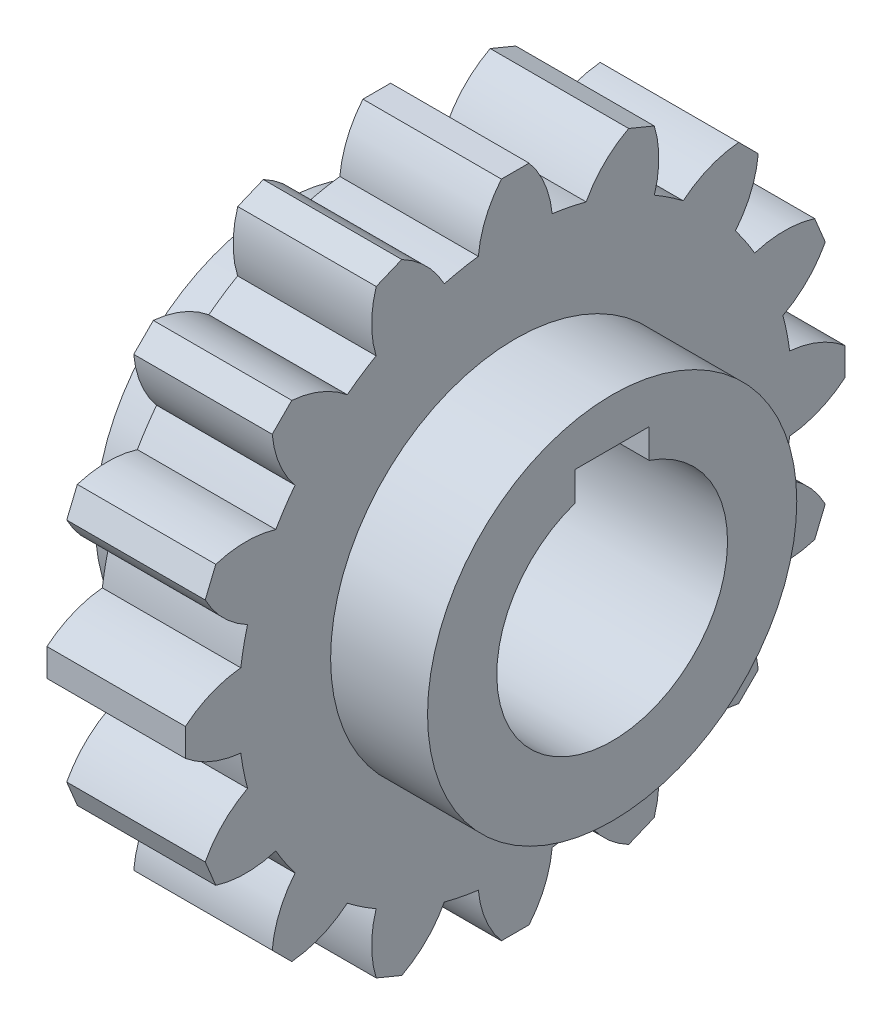
SolidWorks part; units mm, degrees
ref_plane "Front Plane" through (0, 0, 0) normal (0, 0, 1) x (1, 0, 0)
ref_plane "Top Plane" through (0, 0, 0) normal (0, 1, 0) x (1, 0, 0)
ref_plane "Right Plane" through (0, 0, 0) normal (1, 0, 0) x (0, 0, -1)
sketch "Sketch1" plane through (0, 0, 0) normal (1, 0, 0) x (0, 0, -1)
  circle A0 centre (0, 0) radius 30
  dimension "D1" = 60
extrude "Boss-Extrude1" add sketch "Sketch1" along normal mid plane 15
sketch "Sketch2" plane through (7.5, 0, 0) normal (1, 0, 0) x (0, 0, -1)
  line L0 (0, 0) -> (0, 35.7321) construction
  line L1 (-1.5, 35.7321) -> (1.5, 35.7321)
  arc A0 (-4, 29.7321) -> (4, 29.7321) centre (0, 0) ccw
  circle A1 centre (0, 0) radius 30 construction
  arc A2 (-4, 29.7321) -> (-1.5, 35.7321) centre (6.9505, 28.6902) cw
  arc A3 (4, 29.7321) -> (1.5, 35.7321) centre (-6.9505, 28.6902) ccw
  point P11 (0, 35.7321)
  dimension "D4" = 11
  dimension "D1" = 3
  dimension "D2" = 4
  dimension "D3" = 6
extrude "Boss-Extrude2" add sketch "Sketch2" against normal up to surface (15 mm away) up to face at (-7.5, 0, -30)
pattern_circular "CirPattern1" count 16 over 360 about axis through (0, 0, 0) along (1, 0, 0) of "Boss-Extrude2"
sketch "Sketch3" plane through (0, 0, 0) normal (1, 0, 0) x (0, 0, -1)
  circle A0 centre (0, 0) radius 20
  dimension "D1" = 40
extrude "Boss-Extrude3" add sketch "Sketch3" along normal mid plane 36
sketch "Sketch4" plane through (18, 0, 0) normal (1, 0, 0) x (0, 0, -1)
  line L0 (0, 0) -> (0, 15) construction
  line L1 (-4, 15) -> (4, 15)
  line L2 (-4, 15) -> (-4, 11.8427)
  line L3 (4, 15) -> (4, 11.8427)
  arc A0 (-4, 11.8427) -> (4, 11.8427) centre (0, 0) ccw
  point P7 (0, 15)
  dimension "D1" = 25
  dimension "D2" = 8
  dimension "D3" = 15
extrude "Cut-Extrude1" cut sketch "Sketch4" against normal through all
